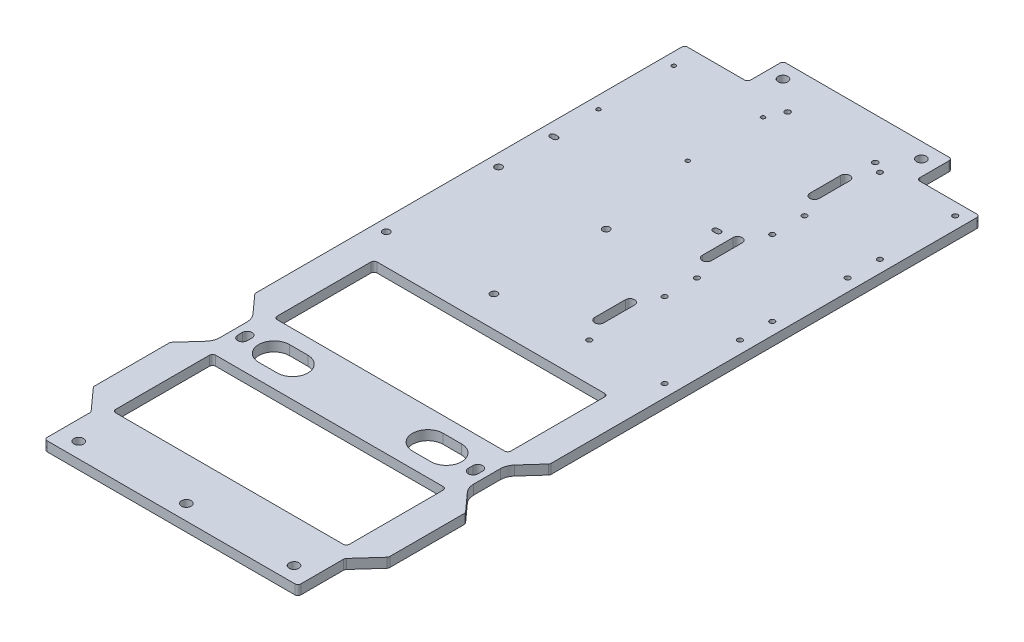
SolidWorks part; units mm, degrees
ref_plane "Front Plane" through (0, 0, 0) normal (0, 0, 1) x (1, 0, 0)
ref_plane "Top Plane" through (0, 0, 0) normal (0, 1, 0) x (1, 0, 0)
ref_plane "Right Plane" through (0, 0, 0) normal (1, 0, 0) x (0, 0, -1)
sketch "Sketch1" plane through (0, 0, 0) normal (0, 1, 0) x (1, 0, 0)
  line L1 (-82.5, -215) -> (82.5, -215)
  line L2 (-82.5, -215) -> (-82.5, 215)
  line L3 (-82.5, 215) -> (82.5, 215)
  line L4 (82.5, -215) -> (82.5, 215)
  line L5 (-82.5, -215) -> (82.5, 215) construction
  line L6 (-82.5, 215) -> (82.5, -215) construction
  point P0 (0, 0)
  dimension "D1" = 165
  dimension "D2" = 430
extrude "Boss-Extrude1" add sketch "Sketch1" along normal blind 6.25
sketch "Sketch2" plane through (0, 6.25, 0) normal (0, 1, 0) x (1, 0, 0)
  line L0 (82.5, 215) -> (-82.5, 215) construction
  line L1 (-55, 192) -> (55, 192)
  line L2 (-55, 192) -> (-55, 238)
  line L3 (-55, 238) -> (55, 238)
  line L4 (55, 192) -> (55, 238)
  line L5 (-55, 192) -> (55, 238) construction
  line L6 (-55, 238) -> (55, 192) construction
  point P0 (0, 215)
  dimension "D1" = 110
  dimension "D2" = 23
extrude "Boss-Extrude2" add sketch "Sketch2" against normal up to surface (6.25 mm away) up to face at (0, 0, 0)
sketch "Sketch3" plane through (0, 6.25, 0) normal (0, 1, 0) x (1, 0, 0)
  line L0 (0, 238) -> (0, 228) construction
  line L1 (55, 238) -> (-55, 238) construction
  line L2 (0, 228) -> (45, 228) construction
  line L3 (0, 228) -> (-45, 228) construction
  circle A0 centre (-45, 228) radius 3.15
  circle A1 centre (45, 228) radius 3.15
  dimension "D3" = 6.3
  dimension "D1" = 45
  dimension "D2" = 10
extrude "Cut-Extrude1" cut sketch "Sketch3" against normal through all
sketch "Sketch5" plane through (0, 6.25, 0) normal (0, 1, 0) x (1, 0, 0)
  line L0 (-45, 228) -> (45, 228) construction
  line L1 (0, 228) -> (0, -92) construction
  line L2 (0, -92) -> (75, -92) construction
  line L3 (0, -92) -> (-75, -92) construction
  line L4 (-75, -93.5) -> (-75, -90.5) construction
  line L5 (-78.15, -93.5) -> (-78.15, -90.5)
  line L6 (-71.85, -93.5) -> (-71.85, -90.5)
  line L7 (75, -93.5) -> (75, -90.5) construction
  line L8 (71.85, -93.5) -> (71.85, -90.5)
  line L9 (78.15, -93.5) -> (78.15, -90.5)
  arc A0 (-78.15, -93.5) -> (-71.85, -93.5) centre (-75, -93.5) ccw
  arc A1 (-71.85, -90.5) -> (-78.15, -90.5) centre (-75, -90.5) ccw
  arc A2 (71.85, -93.5) -> (78.15, -93.5) centre (75, -93.5) ccw
  arc A3 (78.15, -90.5) -> (71.85, -90.5) centre (75, -90.5) ccw
  point P11 (-75, -92)
  point P17 (75, -92)
  dimension "D3" = 3.15
  dimension "D1" = 75
  dimension "D2" = 320
  dimension "D4" = 3
extrude "Cut-Extrude3" cut sketch "Sketch5" against normal through all
sketch "Sketch4" plane through (0, 6.25, 0) normal (0, 1, 0) x (1, 0, 0)
  line L0 (0, 0) -> (0, -39.5) construction
  line L1 (-76, -72) -> (76, -72)
  line L2 (-76, -72) -> (-76, -7)
  line L3 (-76, -7) -> (76, -7)
  line L4 (76, -72) -> (76, -7)
  line L5 (-76, -72) -> (76, -7) construction
  line L6 (-76, -7) -> (76, -72) construction
  line L7 (-76, -177) -> (76, -177)
  line L8 (-76, -177) -> (-76, -112)
  line L9 (-76, -112) -> (76, -112)
  line L10 (76, -177) -> (76, -112)
  line L11 (-76, -177) -> (76, -112) construction
  line L12 (-76, -112) -> (76, -177) construction
  line L13 (0, -39.5) -> (0, -92) construction
  line L14 (0, -92) -> (0, -144.5) construction
  line L15 (0, -92) -> (71.85, -92) construction
  line L16 (71.85, -90.5) -> (71.85, -93.5) construction
  line L17 (0, -92) -> (-71.85, -92) construction
  line L18 (-71.85, -93.5) -> (-71.85, -90.5) construction
  point P0 (0, -39.5)
  point P5 (0, -144.5)
  point P14 (76, -115.2306)
  dimension "D1" = 65
  dimension "D2" = 152
  dimension "D3" = 40
extrude "Cut-Extrude2" cut sketch "Sketch4" against normal through all
sketch "Sketch6" plane through (0, 6.25, 0) normal (0, 1, 0) x (1, 0, 0)
  line L0 (82.5, 0.5) -> (82.5, -79.5)
  line L1 (82.5, -215) -> (82.5, 215) construction
  line L2 (82.5, -79.5) -> (96, -64.5)
  line L3 (96, -64.5) -> (96, -14.5)
  line L4 (96, -14.5) -> (82.5, 0.5)
  line L5 (82.5, -104.5) -> (82.5, -184.5)
  line L6 (82.5, -184.5) -> (96, -169.5)
  line L7 (96, -169.5) -> (96, -119.5)
  line L8 (96, -119.5) -> (82.5, -104.5)
  line L9 (76, -39.5) -> (96, -39.5) construction
  line L10 (76, -72) -> (76, -7) construction
  line L11 (76, -144.5) -> (96, -144.5) construction
  line L12 (76, -177) -> (76, -112) construction
  point P18 (92.9899, -128.7031)
  point P19 (95.5664, -14.0077)
  point P20 (94.9568, -166.042)
  point P21 (96.2784, -59.2692)
  point P22 (92.4581, -12.0952)
  point P23 (91, -15.2566)
  dimension "D1" = 20
  dimension "D2" = 80
  dimension "D3" = 25
  dimension "D4" = 50
extrude "Boss-Extrude3" add sketch "Sketch6" against normal up to surface (6.25 mm away) up to face at (0, 0, 39.5)
sketch "Sketch7" plane through (0, 6.25, 0) normal (0, 1, 0) x (1, 0, 0)
  line L0 (44, -92) -> (56, -92) construction
  line L1 (44, -82) -> (56, -82)
  line L2 (44, -102) -> (56, -102)
  line L3 (56, -92) -> (82.5, -92) construction
  line L4 (82.5, -104.5) -> (82.5, -79.5) construction
  arc A0 (44, -82) -> (44, -102) centre (44, -92) ccw
  arc A1 (56, -102) -> (56, -82) centre (56, -92) ccw
  point P2 (50, -92)
  dimension "D1" = 10
  dimension "D2" = 12
  dimension "D3" = 50
extrude "Cut-Extrude4" cut sketch "Sketch7" against normal through all
sketch "Sketch14" plane through (0, 6.25, 0) normal (0, 1, 0) x (1, 0, 0)
  line L1 (82.5, 215) -> (96, 215)
  line L2 (82.5, 215) -> (82.5, -14.5)
  line L3 (82.5, -14.5) -> (96, -14.5)
  line L4 (96, 215) -> (96, -14.5)
extrude "Boss-Extrude4" add sketch "Sketch14" against normal up to surface (6.25 mm away) up to face at (50, 0, 92)
mirror "Mirror1" about plane through (0, 0, 0) normal (1, 0, 0) of "Boss-Extrude4", "Boss-Extrude3", "Cut-Extrude4"
fillet "Fillet1" radius 2 8 edges at (-76, 3.125, 7) (76, 3.125, 7) (76, 3.125, 177) (-76, 3.125, 177) (-76, 3.125, 112) (76, 3.125, 112) (76, 3.125, 72) (-76, 3.125, 72)
sketch "Sketch8" plane through (0, 6.25, 0) normal (0, 1, 0) x (1, 0, 0)
  line L0 (96, 215) -> (55, 215) construction
  line L1 (39, 158) -> (88, 158) construction
  line L2 (39, 158) -> (39, 207) construction
  line L3 (39, 207) -> (88, 207) construction
  line L4 (88, 158) -> (88, 207) construction
  line L5 (39, 158) -> (88, 207) construction
  line L6 (39, 207) -> (88, 158) construction
  line L8 (96, -64.5) -> (96, 215) construction
  circle A0 centre (39, 207) radius 1.65
  circle A1 centre (88, 207) radius 1.65
  circle A2 centre (88, 158) radius 1.65
  circle A3 centre (39, 158) radius 1.65
  point P0 (63.5, 182.5)
  point P9 (49.2918, 178.6554)
  dimension "D2" = 3.3
  dimension "D1" = 49
  dimension "D3" = 8
  dimension "D4" = 8
extrude "Cut-Extrude5" cut sketch "Sketch8" against normal through all
sketch "Sketch12" plane through (0, 6.25, 0) normal (0, 1, 0) x (1, 0, 0)
  line L0 (39, 207) -> (39, 158) construction
  line L1 (39, 182.5) -> (31, 182.5) construction
  line L2 (31, 172.5) -> (31, 192.5) construction
  line L3 (28, 172.5) -> (28, 192.5)
  line L4 (34, 172.5) -> (34, 192.5)
  arc A0 (28, 172.5) -> (34, 172.5) centre (31, 172.5) ccw
  arc A1 (34, 192.5) -> (28, 192.5) centre (31, 192.5) ccw
  point P8 (31, 182.5)
  dimension "D2" = 3
  dimension "D1" = 20
  dimension "D3" = 8
extrude "Cut-Extrude8" cut sketch "Sketch12" against normal through all
pattern_linear "LPattern1" count 3 spacing 70 along (0, 0, 1) of "Cut-Extrude5", "Cut-Extrude8"
sketch "Sketch9" plane through (0, 6.25, 0) normal (0, 1, 0) x (1, 0, 0)
  line L1 (-88, 13) -> (-18, 13) construction
  line L2 (-88, 13) -> (-88, 86) construction
  line L3 (-88, 86) -> (-18, 86) construction
  line L4 (-18, 13) -> (-18, 86) construction
  line L5 (-88, 13) -> (-18, 86) construction
  line L6 (-88, 86) -> (-18, 13) construction
  line L7 (74, -7) -> (-74, -7) construction
  line L8 (-96, -64.5) -> (-96, 215) construction
  circle A0 centre (-88, 86) radius 2.25
  circle A1 centre (-18, 86) radius 2.25
  circle A2 centre (-88, 13) radius 2.25
  circle A3 centre (-18, 13) radius 2.25
  point P0 (-53, 49.5)
  dimension "D3" = 4.5
  dimension "D1" = 70
  dimension "D2" = 73
  dimension "D4" = 8
  dimension "D5" = 20
extrude "Cut-Extrude6" cut sketch "Sketch9" against normal through all
sketch "Sketch10" plane through (0, 6.25, 0) normal (0, 1, 0) x (1, 0, 0)
  line L0 (-55, 215) -> (-96, 215) construction
  line L1 (-30, 151) -> (-88, 151) construction
  line L2 (-30, 151) -> (-30, 200) construction
  line L3 (-30, 200) -> (-88, 200) construction
  line L4 (-88, 151) -> (-88, 200) construction
  line L5 (-30, 151) -> (-88, 200) construction
  line L6 (-30, 200) -> (-88, 151) construction
  line L8 (-96, -64.5) -> (-96, 215) construction
  circle A0 centre (-88, 200) radius 1.3
  circle A1 centre (-30, 200) radius 1.3
  circle A2 centre (-88, 151) radius 1.3
  circle A3 centre (-30, 151) radius 1.3
  point P0 (-59, 175.5)
  dimension "D3" = 2.6
  dimension "D1" = 58
  dimension "D2" = 49
  dimension "D4" = 15
  dimension "D5" = 8
extrude "Cut-Extrude7" cut sketch "Sketch10" against normal through all
fillet "Fillet2" radius 10 4 edges at (-82.5, 3.125, 104.5) (-82.5, 3.125, 79.5) (82.5, 3.125, 104.5) (82.5, 3.125, 79.5)
sketch "Sketch13" plane through (0, 6.25, 0) normal (0, 1, 0) x (1, 0, 0)
  line L0 (0, -215) -> (0, -205) construction
  line L1 (-82.5, -215) -> (82.5, -215) construction
  line L2 (0, -205) -> (70, -205) construction
  line L3 (0, -205) -> (-70, -205) construction
  circle A0 centre (-70, -205) radius 3.15
  circle A1 centre (70, -205) radius 3.15
  circle A2 centre (0, -205) radius 3.15
  dimension "D2" = 6.3
  dimension "D1" = 10
  dimension "D3" = 70
extrude "Cut-Extrude9" cut sketch "Sketch13" against normal through all
sketch "Sketch15" plane through (0, 6.25, 0) normal (0, 1, 0) x (1, 0, 0)
  line L0 (-87, 121) -> (19, 121) construction
  line L1 (-88, 121) -> (-86, 121) construction
  line L2 (-88, 122.65) -> (-86, 122.65)
  line L3 (-88, 119.35) -> (-86, 119.35)
  line L4 (20, 121) -> (18, 121) construction
  line L5 (20, 119.35) -> (18, 119.35)
  line L6 (20, 122.65) -> (18, 122.65)
  line L7 (-96, -64.5) -> (-96, 215) construction
  arc A0 (-88, 122.65) -> (-88, 119.35) centre (-88, 121) ccw
  arc A1 (-86, 119.35) -> (-86, 122.65) centre (-86, 121) ccw
  arc A2 (20, 119.35) -> (20, 122.65) centre (20, 121) ccw
  arc A3 (18, 122.65) -> (18, 119.35) centre (18, 121) ccw
  circle A4 centre (-88, 86) radius 2.25 construction
  point P4 (-87, 121)
  point P10 (19, 121)
  point P16 (0, 0)
  dimension "D2" = 1.65
  dimension "D1" = 106
  dimension "D3" = 2
  dimension "D4" = 8
  dimension "D5" = 35
extrude "Cut-Extrude10" cut sketch "Sketch15" against normal through all
fillet "Fillet3" radius 2 16 edges at (-96, 3.125, 64.5) (-96, 3.125, 119.5) (-96, 3.125, 169.5) (-82.5, 3.125, 184.5) (-82.5, 3.125, 215) (82.5, 3.125, 215) (82.5, 3.125, 184.5) (96, 3.125, 169.5) (96, 3.125, 119.5) (96, 3.125, 64.5) (-96, 3.125, -215) (96, 3.125, -215) (55, 3.125, -215) (55, 3.125, -238) (-55, 3.125, -238) (-55, 3.125, -215)
sketch "Sketch16" plane through (0, 6.25, 0) normal (0, 1, 0) x (1, 0, 0)
  line L0 (-25, 211) -> (32, 211) construction
  line L1 (-57, 215) -> (-94, 215) construction
  line L2 (-55, 236) -> (-55, 217) construction
  circle A0 centre (-25, 211) radius 1.75
  circle A1 centre (32, 211) radius 1.75
  dimension "D2" = 3.5
  dimension "D4" = 30
  dimension "D1" = 57
  dimension "D3" = 4
extrude "Cut-Extrude11" cut sketch "Sketch16" against normal through all
